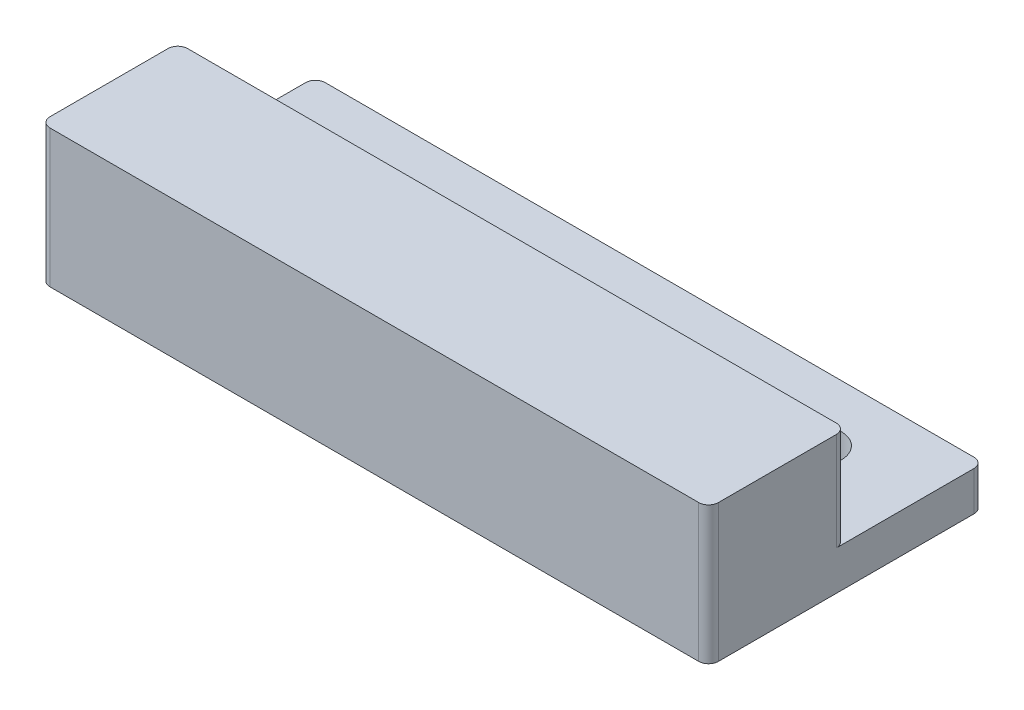
SolidWorks part; units mm, degrees
ref_plane "Front Plane" through (0, 0, 0) normal (0, 0, 1) x (1, 0, 0)
ref_plane "Top Plane" through (0, 0, 0) normal (0, 1, 0) x (1, 0, 0)
ref_plane "Right Plane" through (0, 0, 0) normal (1, 0, 0) x (0, 0, -1)
sketch "Sketch1" plane through (0, 0, 0) normal (0, 1, 0) x (1, 0, 0)
  line L1 (-17, 7) -> (17, 7)
  line L2 (-17, 7) -> (-17, -7)
  line L3 (-17, -7) -> (17, -7)
  line L4 (17, 7) -> (17, -7)
  line L5 (-17, 7) -> (17, -7) construction
  line L6 (-17, -7) -> (17, 7) construction
  point P0 (0, 0)
  dimension "D1" = 34
  dimension "D2" = 14
extrude "Boss-Extrude1" add sketch "Sketch1" along normal blind 2
sketch "Sketch2" plane through (0, 2, 0) normal (0, 1, 0) x (1, 0, 0)
  line L0 (-17, 7) -> (-17, -7) construction
  line L1 (17, -7) -> (-17, -7)
  line L2 (17, -7) -> (17, 0)
  line L3 (17, 0) -> (-17, 0)
  line L4 (-17, -7) -> (-17, 0)
extrude "Boss-Extrude2" add sketch "Sketch2" along normal blind 5
fillet "Fillet1" radius 0.5 6 edges at (17, 3.5, 7) (17, 4.5, 0) (-17, 4.5, 0) (-17, 3.5, 7) (-17, 1, -7) (17, 1, -7)
sketch "Sketch3" plane through (0, 2, 0) normal (0, 1, 0) x (1, 0, 0)
  line L1 (0, 7) -> (0, 0) construction
  line L2 (16.5, 7) -> (-16.5, 7) construction
  line L3 (16.5, 0) -> (-16.5, 0) construction
  circle A0 centre (12, 3.5) radius 1.25
  circle A1 centre (-12, 3.5) radius 1.25
  point P3 (0, 3.5)
  dimension "D1" = 2.5
  dimension "D2" = 12
extrude "Cut-Extrude1" cut sketch "Sketch3" against normal up to next
